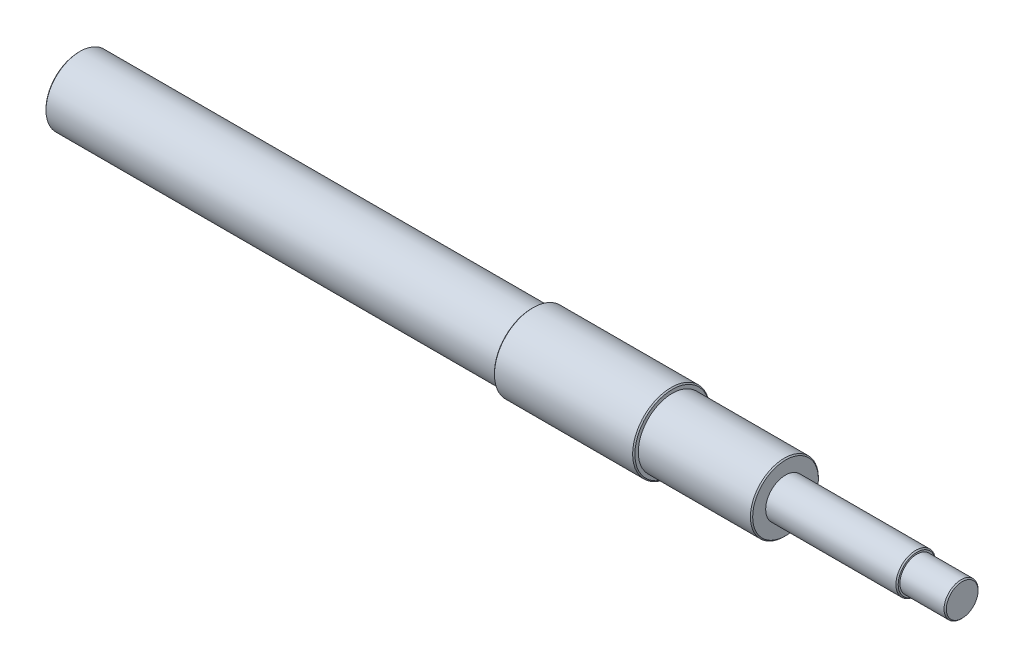
SolidWorks part; units mm, degrees
ref_plane "Front Plane" through (0, 0, 0) normal (0, 0, 1) x (1, 0, 0)
ref_plane "Top Plane" through (0, 0, 0) normal (0, 1, 0) x (1, 0, 0)
ref_plane "Right Plane" through (0, 0, 0) normal (1, 0, 0) x (0, 0, -1)
sketch "Sketch1" plane through (0, 0, 0) normal (0, 0, 1) x (1, 0, 0)
  line L8 (-25.6, 3) -> (-15.6, 3)
  line L9 (-15.6, 3) -> (-15.6, 1.75)
  line L10 (-15.6, 1.75) -> (-4, 1.75)
  line L11 (-4, 1.75) -> (-4, 1.5)
  line L12 (-4, 1.5) -> (0, 1.5)
  line L13 (0, 1.5) -> (0, 0)
  line L14 (0, 0) -> (17.0542, 0) construction
  line L15 (0, 0) -> (-78, 0)
  line L16 (-78, 0) -> (-78, 3)
  line L17 (-78, 3) -> (-38, 3)
  line L18 (-38, 3) -> (-38, 3.4)
  line L19 (-38, 3.4) -> (-25.6, 3.4)
  line L20 (-25.6, 3.4) -> (-25.6, 3)
  line L21 (9.4704, 0) -> (-126.0086, 0) construction
  dimension "D1" = 1.5
  dimension "D2" = 1.75
  dimension "D3" = 3
  dimension "D4" = 11.6
  dimension "D5" = 4
  dimension "D6" = 10
  dimension "D7" = 78
  dimension "D8" = 40
  dimension "D9" = 3
  dimension "D10" = 3.4
revolve "Revolve1" add sketch "Sketch1" angle 360 about L14
chamfer "Chamfer1" distance 0.1 angle 45 6 edges at (0, 0, 1.5) (-4, 0, 1.75) (-38, 0, 3.4) (-25.6, 0, 3.4) (-15.6, 0, 3) (-78, 0, 3)
